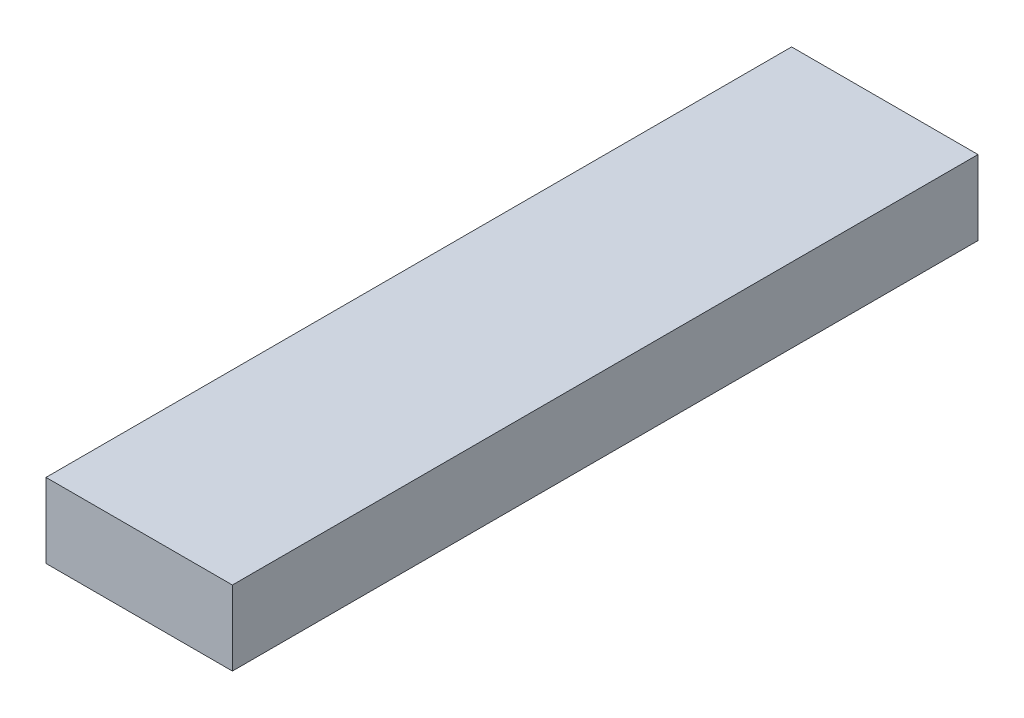
SolidWorks part; units mm, degrees
ref_plane "Front Plane" through (0, 0, 0) normal (0, 0, 1) x (1, 0, 0)
ref_plane "Top Plane" through (0, 0, 0) normal (0, 1, 0) x (1, 0, 0)
ref_plane "Right Plane" through (0, 0, 0) normal (1, 0, 0) x (0, 0, -1)
sketch "Sketch1" plane through (0, 0, 0) normal (0, 1, 0) x (1, 0, 0)
  line L1 (0, 0) -> (2.5, 0)
  line L2 (0, 0) -> (0, 10)
  line L3 (0, 10) -> (2.5, 10)
  line L4 (2.5, 0) -> (2.5, 10)
  dimension "D1" = 10
  dimension "D2" = 2.5
extrude "Boss-Extrude1" add sketch "Sketch1" along normal blind 1
